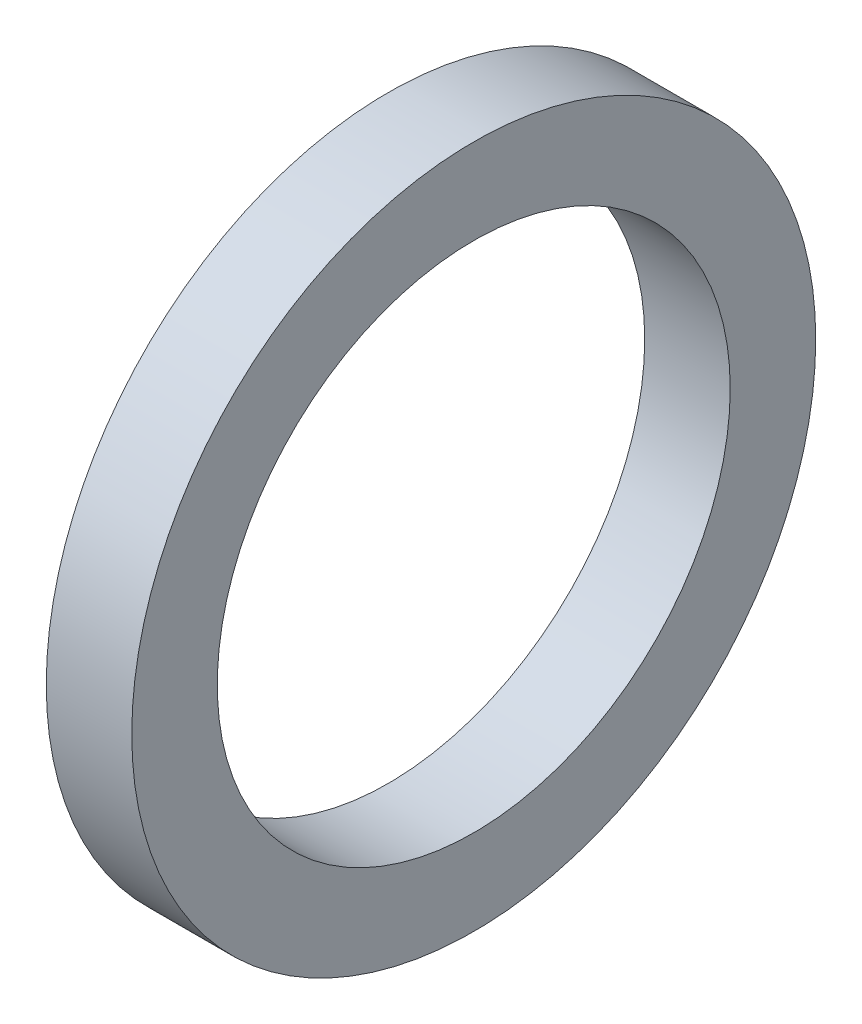
SolidWorks part; units mm, degrees
ref_plane "Front Plane" through (0, 0, 0) normal (0, 0, 1) x (1, 0, 0)
ref_plane "Top Plane" through (0, 0, 0) normal (0, 1, 0) x (1, 0, 0)
ref_plane "Right Plane" through (0, 0, 0) normal (1, 0, 0) x (0, 0, -1)
sketch "Sketch1" plane through (0, 0, 0) normal (1, 0, 0) x (0, 0, -1)
  circle A0 centre (0, 0) radius 4.7625
  circle A1 centre (0, 0) radius 6.35
  dimension "D1" = 9.525
  dimension "D2" = 12.7
extrude "Boss-Extrude1" add sketch "Sketch1" along normal blind 1.5875
